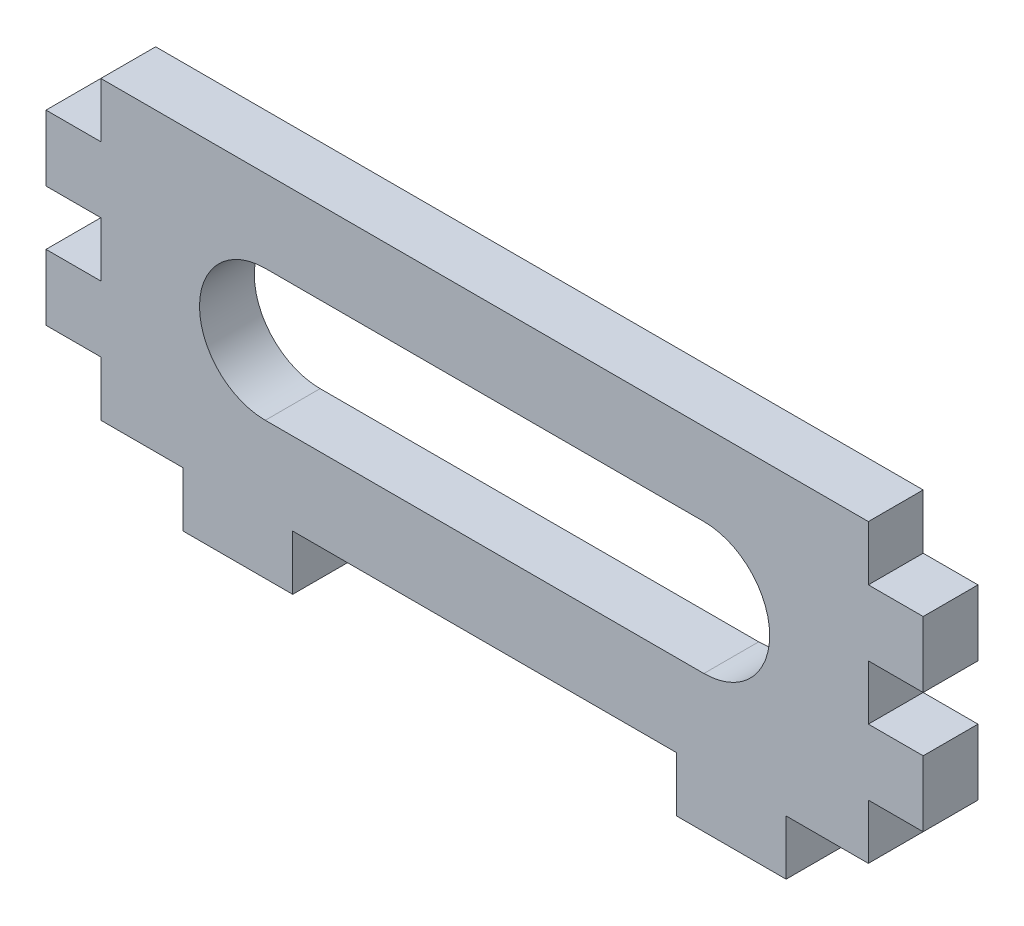
SolidWorks part; units mm, degrees
material "Balsa"
ref_plane "Plan de face" through (0, 0, 0) normal (0, 0, 1) x (1, 0, 0)
ref_plane "Plan de dessus" through (0, 0, 0) normal (0, 1, 0) x (1, 0, 0)
ref_plane "Plan de droite" through (0, 0, 0) normal (1, 0, 0) x (0, 0, -1)
sketch "Esquisse1" plane through (0, 0, 0) normal (0, 0, 1) x (1, 0, 0)
  line L1 (-201.1746, 170.4211) -> (-121.1746, 170.4211)
  line L2 (-201.1746, 170.4211) -> (-201.1746, 143.4211)
  line L3 (-201.1746, 143.4211) -> (-121.1746, 143.4211)
  line L4 (-121.1746, 170.4211) -> (-121.1746, 143.4211)
extrude "Boss.-Extru.1" add sketch "Esquisse1" against normal blind 5
sketch "Esquisse2" plane through (0, 0, 0) normal (0, 0, 1) x (1, 0, 0)
  line L0 (-121.1746, 170.4211) -> (-201.1746, 170.4211) construction
  line L1 (-126.1746, 170.4211) -> (-121.1746, 170.4211)
  line L2 (-126.1746, 170.4211) -> (-126.1746, 165.4211)
  line L3 (-126.1746, 165.4211) -> (-121.1746, 165.4211)
  line L4 (-121.1746, 170.4211) -> (-121.1746, 165.4211)
  line L5 (-121.1746, 143.4211) -> (-121.1746, 170.4211) construction
  line L6 (-201.1746, 143.4211) -> (-121.1746, 143.4211) construction
  line L7 (-126.1746, 143.4211) -> (-121.1746, 143.4211)
  line L8 (-126.1746, 143.4211) -> (-126.1746, 148.4211)
  line L9 (-126.1746, 148.4211) -> (-121.1746, 148.4211)
  line L10 (-121.1746, 143.4211) -> (-121.1746, 148.4211)
  line L11 (-161.1746, 223.4211) -> (-161.1746, 138.4211) construction
  line L12 (-126.1746, 159.4211) -> (-121.1746, 159.4211)
  line L13 (-126.1746, 159.4211) -> (-126.1746, 154.4211)
  line L14 (-126.1746, 154.4211) -> (-121.1746, 154.4211)
  line L15 (-121.1746, 159.4211) -> (-121.1746, 154.4211)
  line L16 (-201.1746, 159.4211) -> (-201.1746, 154.4211)
  line L17 (-196.1746, 154.4211) -> (-201.1746, 154.4211)
  line L18 (-196.1746, 159.4211) -> (-196.1746, 154.4211)
  line L19 (-196.1746, 159.4211) -> (-201.1746, 159.4211)
  line L20 (-201.1746, 143.4211) -> (-201.1746, 148.4211)
  line L21 (-196.1746, 148.4211) -> (-201.1746, 148.4211)
  line L22 (-196.1746, 143.4211) -> (-196.1746, 148.4211)
  line L23 (-196.1746, 143.4211) -> (-201.1746, 143.4211)
  line L24 (-201.1746, 170.4211) -> (-201.1746, 165.4211)
  line L25 (-196.1746, 165.4211) -> (-201.1746, 165.4211)
  line L26 (-196.1746, 170.4211) -> (-196.1746, 165.4211)
  line L27 (-196.1746, 170.4211) -> (-201.1746, 170.4211)
  line L28 (-181.1746, 156.9211) -> (-141.1746, 156.9211) construction
  line L29 (-181.1746, 162.9211) -> (-141.1746, 162.9211)
  line L30 (-181.1746, 150.9211) -> (-141.1746, 150.9211)
  arc A0 (-181.1746, 162.9211) -> (-181.1746, 150.9211) centre (-181.1746, 156.9211) ccw
  arc A1 (-141.1746, 150.9211) -> (-141.1746, 162.9211) centre (-141.1746, 156.9211) ccw
  point P34 (-161.1746, 156.9211)
  dimension "D8" = 6
  dimension "D1" = 5
  dimension "D2" = 5
  dimension "D3" = 5
  dimension "D4" = 5
  dimension "D5" = 6
  dimension "D6" = 6
  dimension "D7" = 40
  dimension "D9" = 13.5
extrude "Créneaux -" cut sketch "Esquisse2" against normal blind 5
sketch "Esquisse3" plane through (0, 0, 0) normal (0, 0, 1) x (1, 0, 0)
  line L0 (-161.1746, 223.4211) -> (-161.1746, 138.4211) construction
  line L1 (-196.1746, 143.4211) -> (-126.1746, 143.4211) construction
  line L2 (-188.6746, 143.4211) -> (-178.6746, 143.4211)
  line L3 (-188.6746, 143.4211) -> (-188.6746, 138.4211)
  line L4 (-188.6746, 138.4211) -> (-178.6746, 138.4211)
  line L5 (-178.6746, 143.4211) -> (-178.6746, 138.4211)
  line L6 (-143.6746, 143.4211) -> (-143.6746, 138.4211)
  line L7 (-133.6746, 138.4211) -> (-143.6746, 138.4211)
  line L8 (-133.6746, 143.4211) -> (-133.6746, 138.4211)
  line L9 (-133.6746, 143.4211) -> (-143.6746, 143.4211)
  dimension "D1" = 5
  dimension "D2" = 10
  dimension "D3" = 35
extrude "Boss.-Extru.2" add sketch "Esquisse3" against normal blind 5
